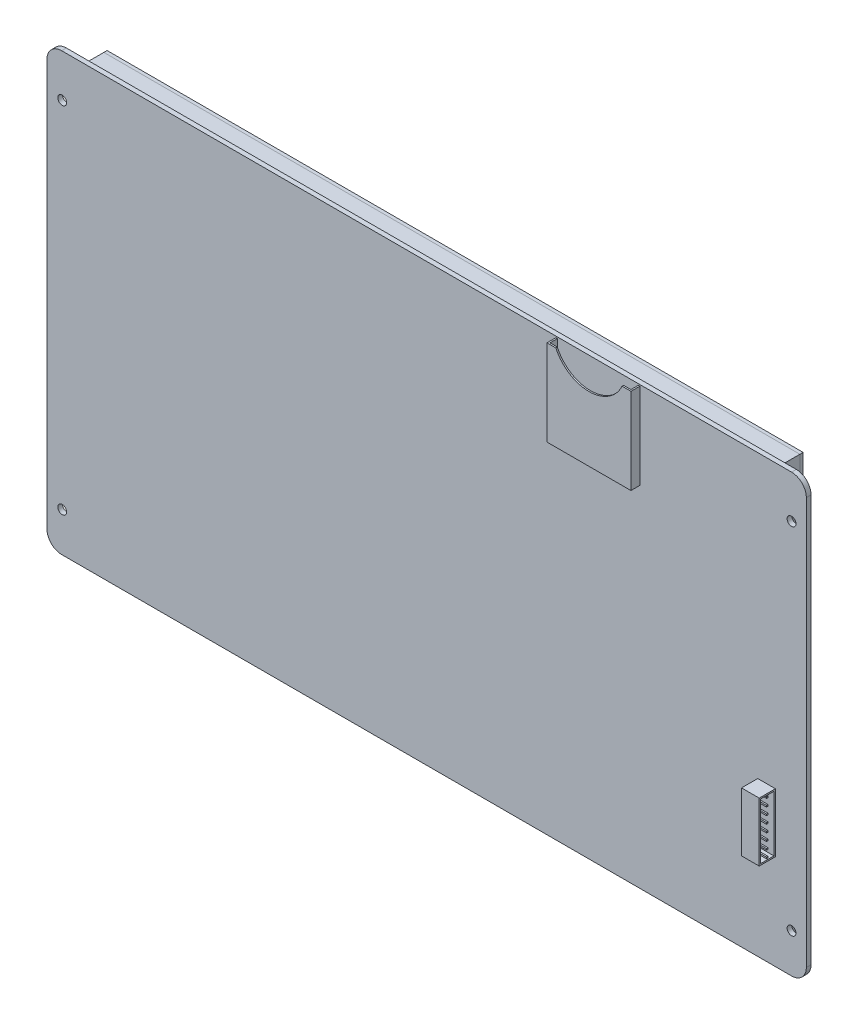
SolidWorks part; units mm, degrees
ref_plane "前视基准面" through (0, 0, 0) normal (0, 0, 1) x (1, 0, 0)
ref_plane "上视基准面" through (0, 0, 0) normal (0, 1, 0) x (1, 0, 0)
ref_plane "右视基准面" through (0, 0, 0) normal (1, 0, 0) x (0, 0, -1)
sketch "草图1" plane through (0, 0, 0) normal (0, 0, 1) x (1, 0, 0)
  line L0 (-144.5066, 0) -> (161.1709, 0) construction
  line L1 (-128.95, 74.1) -> (128.95, 74.1)
  line L2 (-128.95, 74.1) -> (-128.95, -74.1)
  line L3 (-128.95, -74.1) -> (128.95, -74.1)
  line L4 (128.95, 74.1) -> (128.95, -74.1)
  line L5 (0, 107.2959) -> (0, -142.0898) construction
  dimension "D1" = 257.9
  dimension "D2" = 148.2
extrude "凸台-拉伸1" add sketch "草图1" along normal blind 1.6
fillet "圆角1" radius 5 4 edges at (-128.95, 74.1, 0.8) (128.95, 74.1, 0.8) (128.95, -74.1, 0.8) (-128.95, -74.1, 0.8)
sketch "草图2" plane through (0, 0, 0) normal (0, 0, 1) x (1, 0, 0)
  line L0 (-164.9706, -0.57) -> (171.4976, -0.57) construction
  line L1 (0.08, 100.0267) -> (0.08, -104.2693) construction
  line L2 (128.95, -69.1) -> (128.95, 69.1) construction
  line L3 (123.95, 74.1) -> (-123.95, 74.1) construction
  circle A0 centre (-123.77, 59.63) radius 1.5
  circle A1 centre (123.93, 59.63) radius 1.5
  circle A2 centre (123.93, -60.77) radius 1.5
  circle A3 centre (-123.77, -60.77) radius 1.5
  dimension "D1" = 3
  dimension "D2" = 120.4
  dimension "D3" = 247.7
  dimension "D4" = 5.02
  dimension "D5" = 14.47
extrude "固定孔" cut sketch "草图2" along normal blind 1.6
sketch "草图3" plane through (0, 0, 0) normal (0, 0, -1) x (-1, 0, 0)
  line L0 (-152.5693, 0.07) -> (159.4226, 0.07) construction
  line L1 (-118.27, 72.27) -> (118.13, 72.27)
  line L2 (-118.27, 72.27) -> (-118.27, -72.13)
  line L3 (-118.27, -72.13) -> (118.13, -72.13)
  line L4 (118.13, 72.27) -> (118.13, -72.13)
  line L5 (-0.07, 91.2152) -> (-0.07, -110.4699) construction
  circle A0 centre (-123.93, 59.63) radius 1.5 construction
  dimension "D3" = 5.66
  dimension "D1" = 236.4
  dimension "D2" = 144.4
  dimension "D4" = 12.64
extrude "液晶压片厚" add sketch "草图3" along normal blind 6.4
sketch "草图4" plane through (0, 0, -6.4) normal (0, 0, -1) x (-1, 0, 0)
  line L0 (-158.1172, -0.02) -> (155.5064, -0.02) construction
  line L1 (-114.03, 63.88) -> (111.87, 63.88)
  line L2 (-114.03, 63.88) -> (-114.03, -63.92)
  line L3 (-114.03, -63.92) -> (111.87, -63.92)
  line L4 (111.87, 63.88) -> (111.87, -63.92)
  line L5 (-1.08, 89.9098) -> (-1.08, -103.9429) construction
  line L6 (-118.27, -72.13) -> (118.13, -72.13) construction
  line L7 (-118.27, 72.27) -> (-118.27, -72.13) construction
  line L8 (118.13, 72.27) -> (-118.27, 72.27) construction
  line L9 (118.13, -72.13) -> (118.13, 72.27) construction
  line L10 (-118.27, -72.13) -> (118.13, -72.13)
  line L11 (-118.27, 72.27) -> (-118.27, -72.13)
  line L12 (118.13, 72.27) -> (-118.27, 72.27)
  line L13 (118.13, -72.13) -> (118.13, 72.27)
  circle A0 centre (-123.93, 59.63) radius 1.5 construction
  dimension "D1" = 225.9
  dimension "D2" = 127.8
  dimension "D3" = 4.25
  dimension "D4" = 9.9
extrude "铁框架" add sketch "草图4" along normal blind 0.5
sketch "草图5" plane through (0, 0, -6.4) normal (0, 0, -1) x (-1, 0, 0)
  line L0 (-1.08, 106.0487) -> (-1.08, -119.9355) construction
  line L1 (-112.43, 62.63) -> (110.27, 62.63)
  line L2 (-112.43, 62.63) -> (-112.43, -62.67)
  line L3 (-112.43, -62.67) -> (110.27, -62.67)
  line L4 (110.27, 62.63) -> (110.27, -62.67)
  line L5 (-179.6686, -0.02) -> (149.5044, -0.02) construction
  circle A1 centre (-123.93, 59.63) radius 1.5 construction
  dimension "D4" = 3
  dimension "D3" = 11.5
  dimension "D1" = 222.7
  dimension "D2" = 125.3
extrude "显示区域" add sketch "草图5" along normal blind 0.5
sketch "草图6" plane through (0, 0, -6.4) normal (0, 0, -1) x (-1, 0, 0)
  line L0 (111.87, 63.88) -> (-114.03, 63.88) construction
  line L1 (110.27, 62.63) -> (-112.43, 62.63) construction
  line L2 (-114.03, 63.88) -> (-114.03, -63.92) construction
  line L3 (-112.43, 62.63) -> (-112.43, -62.67) construction
  line L4 (-114.03, -63.92) -> (111.87, -63.92) construction
  line L5 (-112.43, -62.67) -> (110.27, -62.67) construction
  line L6 (111.87, -63.92) -> (111.87, 63.88) construction
  line L7 (110.27, -62.67) -> (110.27, 62.63) construction
  line L8 (111.87, 63.88) -> (-114.03, 63.88)
  line L9 (110.27, 62.63) -> (-112.43, 62.63)
  line L10 (-114.03, 63.88) -> (-114.03, -63.92)
  line L11 (-112.43, 62.63) -> (-112.43, -62.67)
  line L12 (-114.03, -63.92) -> (111.87, -63.92)
  line L13 (-112.43, -62.67) -> (110.27, -62.67)
  line L14 (111.87, -63.92) -> (111.87, 63.88)
  line L15 (110.27, -62.67) -> (110.27, 62.63)
extrude "显示过渡区" add sketch "草图6" along normal blind 0.4
ref_plane "显示中心x_距原中心右偏移0.05" through (1.08, 0, 0) normal (1, 0, 0) x (0, 0, -1)
ref_plane "显示中心y-距原中心上偏称0.05" through (0, -0.02, 0) normal (0, 1, 0) x (1, 0, 0)
sketch "草图7" plane through (0, 0, 1.6) normal (0, 0, 1) x (1, 0, 0)
  line L0 (136.8543, -31.77) -> (52.6887, -31.77) construction
  line L1 (112.45, -21.77) -> (118.45, -21.77)
  line L2 (112.45, -21.77) -> (112.45, -41.77)
  line L3 (112.45, -41.77) -> (118.45, -41.77)
  line L4 (118.45, -21.77) -> (118.45, -41.77)
  line L5 (128.95, -69.1) -> (128.95, 69.1) construction
  circle A0 centre (123.93, 59.63) radius 1.5 construction
  circle A1 centre (123.93, -60.77) radius 1.5 construction
  dimension "D1" = 6
  dimension "D2" = 20
  dimension "D3" = 29
  dimension "D4" = 10.5
extrude "凸台-拉伸4" add sketch "草图7" along normal blind 5.5
sketch "草图8" plane through (118.45, 0, 0) normal (1, 0, 0) x (0, 0, -1)
  line L0 (-7.1, -41.77) -> (-7.1, -21.77) construction
  line L1 (-6.6, -22.27) -> (-2.1, -22.27)
  line L2 (-6.6, -22.27) -> (-6.6, -41.27)
  line L3 (-6.6, -41.27) -> (-2.1, -41.27)
  line L4 (-2.1, -22.27) -> (-2.1, -41.27)
  line L5 (-7.1, -21.77) -> (-1.6, -21.77) construction
  line L6 (-1.6, -69.1) -> (-1.6, 69.1) construction
  line L7 (-7.1, -41.77) -> (-1.6, -41.77) construction
  dimension "D1" = 0.5
  dimension "D2" = 0.5
  dimension "D3" = 0.5
  dimension "D4" = 0.5
extrude "切除-拉伸1" cut sketch "草图8" against normal blind 5
sketch "草图9" plane through (113.45, 0, 0) normal (1, 0, 0) x (0, 0, -1)
  line L0 (-4.35, 44.2351) -> (-4.35, 15.8893) construction
  line L1 (-9.9211, -31.77) -> (11.4481, -31.77) construction
  line L2 (-7.1, -21.77) -> (-1.6, -21.77) construction
  line L3 (-7.1, -41.77) -> (-1.6, -41.77) construction
  line L4 (-7.1, -41.77) -> (-7.1, -21.77) construction
  line L5 (-1.6, -41.77) -> (-1.6, -21.77) construction
  line L6 (-5.1262, -30.5) -> (-3.1287, -30.5) construction
  line L7 (-4.6, -30.25) -> (-4.1, -30.25)
  line L8 (-4.6, -30.25) -> (-4.6, -30.75)
  line L9 (-4.6, -30.75) -> (-4.1, -30.75)
  line L10 (-4.1, -30.25) -> (-4.1, -30.75)
  line L11 (-4.6, -27.71) -> (-4.1, -27.71)
  line L12 (-4.6, -27.71) -> (-4.6, -28.21)
  line L13 (-4.6, -28.21) -> (-4.1, -28.21)
  line L14 (-4.1, -27.71) -> (-4.1, -28.21)
  line L15 (-5.1262, -27.96) -> (-3.1287, -27.96) construction
  line L16 (-4.6, -25.17) -> (-4.1, -25.17)
  line L17 (-4.6, -25.17) -> (-4.6, -25.67)
  line L18 (-4.6, -25.67) -> (-4.1, -25.67)
  line L19 (-4.1, -25.17) -> (-4.1, -25.67)
  line L20 (-5.1262, -25.42) -> (-3.1287, -25.42) construction
  line L21 (-4.6, -22.63) -> (-4.1, -22.63)
  line L22 (-4.6, -22.63) -> (-4.6, -23.13)
  line L23 (-4.6, -23.13) -> (-4.1, -23.13)
  line L24 (-4.1, -22.63) -> (-4.1, -23.13)
  line L25 (-5.1262, -22.88) -> (-3.1287, -22.88) construction
  line L26 (-5.1262, -40.66) -> (-3.1287, -40.66) construction
  line L27 (-5.1262, -38.12) -> (-3.1287, -38.12) construction
  line L28 (-5.1262, -35.58) -> (-3.1287, -35.58) construction
  line L29 (-5.1262, -33.04) -> (-3.1287, -33.04) construction
  line L30 (-4.1, -40.91) -> (-4.1, -40.41)
  line L31 (-4.6, -40.41) -> (-4.1, -40.41)
  line L32 (-4.6, -40.91) -> (-4.6, -40.41)
  line L33 (-4.6, -40.91) -> (-4.1, -40.91)
  line L34 (-4.1, -38.37) -> (-4.1, -37.87)
  line L35 (-4.6, -37.87) -> (-4.1, -37.87)
  line L36 (-4.6, -38.37) -> (-4.6, -37.87)
  line L37 (-4.6, -38.37) -> (-4.1, -38.37)
  line L38 (-4.1, -35.83) -> (-4.1, -35.33)
  line L39 (-4.6, -35.33) -> (-4.1, -35.33)
  line L40 (-4.6, -35.83) -> (-4.6, -35.33)
  line L41 (-4.6, -35.83) -> (-4.1, -35.83)
  line L42 (-4.1, -33.29) -> (-4.1, -32.79)
  line L43 (-4.6, -32.79) -> (-4.1, -32.79)
  line L44 (-4.6, -33.29) -> (-4.6, -32.79)
  line L45 (-4.6, -33.29) -> (-4.1, -33.29)
  dimension "D2" = 2.54
  dimension "D3" = 0.5
  dimension "D4" = 0.5
  dimension "D1" = 4
extrude "凸台-拉伸5" add sketch "草图9" along normal blind 5
sketch "草图10" plane through (0, 0, 1.6) normal (0, 0, 1) x (1, 0, 0)
  line L0 (58.13, 19.8454) -> (58.13, 97.937) construction
  line L2 (46.88, 73.6) -> (43.88, 73.6)
  line L3 (34.8341, 66.4) -> (83.1127, 66.4) construction
  line L4 (43.88, 73.6) -> (43.88, 44.4)
  line L5 (43.88, 44.4) -> (72.38, 44.4)
  line L6 (72.38, 73.6) -> (72.38, 44.4)
  line L7 (69.38, 73.6) -> (72.38, 73.6)
  line L8 (123.95, 74.1) -> (-123.95, 74.1) construction
  arc A0 (46.88, 73.6) -> (69.38, 73.6) centre (58.13, 78.7891) ccw
  circle A1 centre (123.93, 59.63) radius 1.5 construction
  point P11 (58.13, 44.4)
  dimension "D6" = 7.2
  dimension "D1" = 65.8
  dimension "D2" = 28.5
  dimension "D3" = 22.5
  dimension "D4" = 0.5
  dimension "D5" = 29.2
extrude "凸台-拉伸6" add sketch "草图10" along normal blind 3
sketch "草图11" plane through (0, 73.6, 0) normal (0, 1, 0) x (1, 0, 0)
  line L0 (123.95, -1.6) -> (-123.95, -1.6) construction
  line L1 (44.38, -1.6) -> (71.88, -1.6)
  line L2 (44.38, -1.6) -> (44.38, -4.1)
  line L3 (44.38, -4.1) -> (71.88, -4.1)
  line L4 (71.88, -1.6) -> (71.88, -4.1)
  line L5 (72.38, -4.6) -> (69.38, -4.6) construction
  line L6 (72.38, -4.6) -> (72.38, -1.6) construction
  line L7 (43.88, -4.6) -> (43.88, -1.6) construction
  point P8 (72.38, -3.1)
  dimension "D1" = 0.5
  dimension "D2" = 0.5
  dimension "D3" = 0.5
extrude "切除-拉伸2" cut sketch "草图11" against normal blind 25
sketch "草图14" plane through (0, 0, -6.9) normal (0, 0, -1) x (-1, 0, 0)
  line L0 (-114.03, -63.92) -> (111.87, -63.92) construction
  line L1 (-114.03, 63.88) -> (-114.03, -63.92) construction
  line L2 (111.87, 63.88) -> (-114.03, 63.88) construction
  line L3 (111.87, -63.92) -> (111.87, 63.88) construction
  line L4 (118.13, -72.13) -> (118.13, 72.27) construction
  line L5 (118.13, 72.27) -> (-118.27, 72.27) construction
  line L6 (-118.27, 72.27) -> (-118.27, -72.13) construction
  line L7 (-118.27, -72.13) -> (118.13, -72.13) construction
  line L8 (-114.03, -63.92) -> (111.87, -63.92)
  line L9 (-114.03, 63.88) -> (-114.03, -63.92)
  line L10 (111.87, 63.88) -> (-114.03, 63.88)
  line L11 (111.87, -63.92) -> (111.87, 63.88)
  line L12 (118.13, -72.13) -> (118.13, 72.27)
  line L13 (118.13, 72.27) -> (-118.27, 72.27)
  line L14 (-118.27, 72.27) -> (-118.27, -72.13)
  line L15 (-118.27, -72.13) -> (118.13, -72.13)
extrude "触摸屏高度" add sketch "草图14" along normal blind 1.1 separate body
